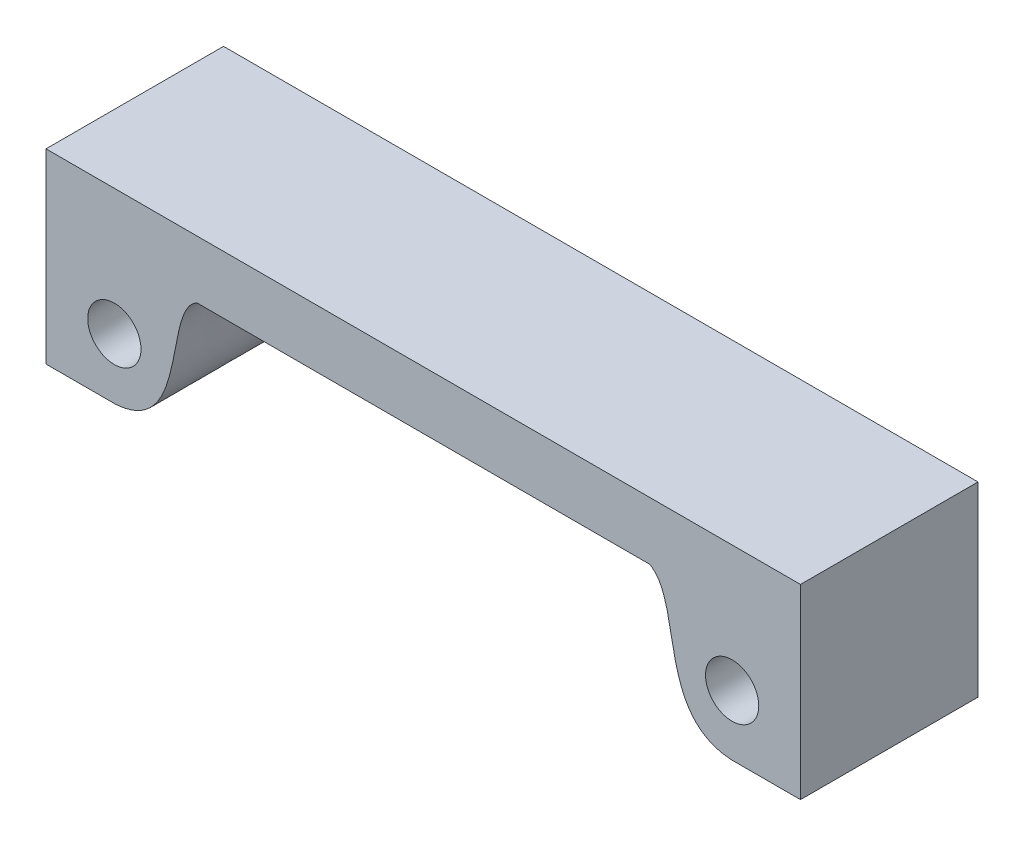
SolidWorks part; units mm, degrees
ref_plane "Спереди" through (0, 0, 0) normal (0, 0, 1) x (1, 0, 0)
ref_plane "Сверху" through (0, 0, 0) normal (0, 1, 0) x (1, 0, 0)
ref_plane "Справа" through (0, 0, 0) normal (1, 0, 0) x (0, 0, -1)
sketch "Эскиз3" plane through (0, 0, 0) normal (0, 0, 1) x (1, 0, 0)
  line L1 (-42.5, 11) -> (42.5, 11)
  line L2 (-42.5, 11) -> (-42.5, -10)
  line L3 (-42.5, -10) -> (42.5, -10)
  line L4 (42.5, 11) -> (42.5, -10)
extrude "Вытянуть2" add sketch "Эскиз3" along normal blind 20
sketch "Эскиз4" plane through (0, 0, 20) normal (0, 0, 1) x (1, 0, 0)
  circle A0 centre (-34.8, -3.2) radius 3
  circle A1 centre (34.8, -3.2) radius 3
extrude "Вырез-Вытянуть2" cut sketch "Эскиз4" against normal through all
sketch "Эскиз6" plane through (0, 0, 20) normal (0, 0, 1) x (1, 0, 0)
  line L0 (-34.6379, -10) -> (34.6379, -10)
  line L1 (-42.5, -10) -> (42.5, -10) construction
  line L2 (-25.5, 4.4724) -> (25.5, 4.4724)
  line L3 (0, 10) -> (0, 12.5927) construction
  arc A2 (-40.9703, -12.0247) -> (-26.258, 2.6875) centre (-42.7551, 4.4724) ccw construction
  spline S0 degree 3 poles (-25.5, 4.4724) (-29.3282, 2.4275) (-26.2629, -9.3807) (-34.6379, -10) knots 0 0 0 0 1 1 1 1
  spline S1 degree 3 poles (25.5, 4.4724) (29.3282, 2.4275) (26.2629, -9.3807) (34.6379, -10) knots 0 0 0 0 1 1 1 1
  point P4 (0, -10)
extrude "Вырез-Вытянуть3" cut sketch "Эскиз6" against normal through all
